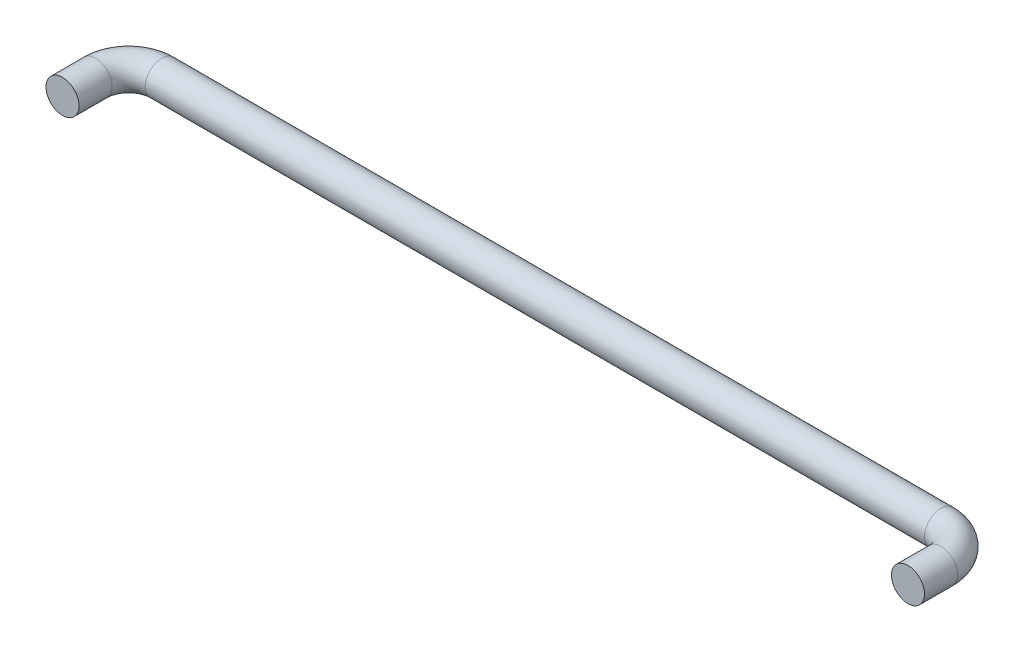
SolidWorks part; units mm, degrees
ref_plane "Front Plane" through (0, 0, 0) normal (0, 0, 1) x (1, 0, 0)
ref_plane "Top Plane" through (0, 0, 0) normal (0, 1, 0) x (1, 0, 0)
ref_plane "Right Plane" through (0, 0, 0) normal (1, 0, 0) x (0, 0, -1)
sketch "Sketch1" plane through (0, 0, 0) normal (0, 1, 0) x (1, 0, 0)
  line L0 (0, 0) -> (0, 50)
  line L1 (50, 100) -> (1228.6, 100)
  line L2 (1278.6, 50) -> (1278.6, 0)
  arc A0 (1228.6, 100) -> (1278.6, 50) centre (1228.6, 50) cw
  arc A1 (50, 100) -> (0, 50) centre (50, 50) ccw
  point P8 (1278.6, 100)
  point P11 (0, 100)
  dimension "D4" = 50
  dimension "D1" = 100
  dimension "D2" = 1278.6
  dimension "D3" = 100
sketch "Sketch2" plane through (0, 0, 0) normal (0, 0, 1) x (1, 0, 0)
  circle A0 centre (0, 0) radius 25
  dimension "D1" = 50
sweep "Sweep1" add profiles "Sketch2" path "Sketch1"
